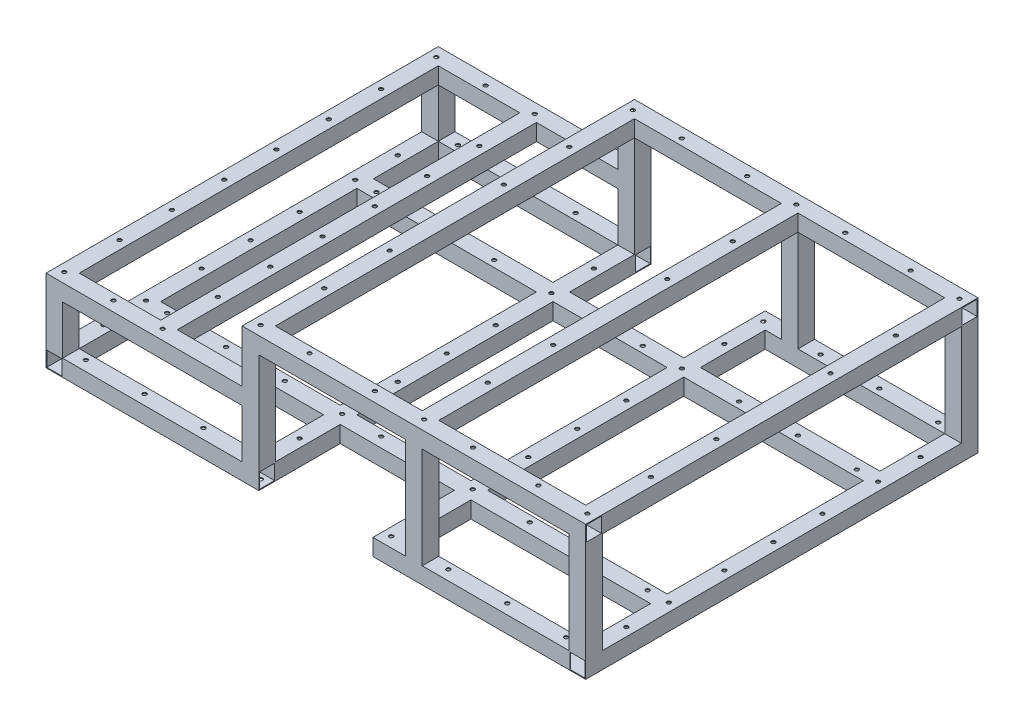
SolidWorks part; units mm, degrees
ref_plane "Front Plane" through (0, 0, 0) normal (0, 0, 1) x (1, 0, 0)
ref_plane "Top Plane" through (0, 0, 0) normal (0, 1, 0) x (1, 0, 0)
ref_plane "Right Plane" through (0, 0, 0) normal (1, 0, 0) x (0, 0, -1)
sketch "Sketch1" plane through (0, 0, 0) normal (0, 1, 0) x (1, 0, 0)
  line L0 (0, 0) -> (-415.7612, 0) construction
  line L1 (-387.3, -150) -> (387.3, -150)
  line L2 (-387.3, -150) -> (-387.3, -175.4)
  line L3 (-387.3, -175.4) -> (387.3, -175.4)
  line L4 (387.3, -150) -> (387.3, -175.4)
  line L9 (0, 0) -> (0, -321.173) construction
  line L10 (387.3, 150) -> (387.3, 175.4)
  line L11 (-387.3, 175.4) -> (387.3, 175.4)
  line L12 (-387.3, 150) -> (-387.3, 175.4)
  line L13 (-387.3, 150) -> (387.3, 150)
  point P7 (0, -175.4)
  dimension "D1" = 774.6
  dimension "D2" = 25.4
  dimension "D3" = 150
  dimension "D4" = 0
extrude "Boss-Extrude1" add sketch "Sketch1" along normal blind 25.4
sketch "Sketch4" plane through (-387.3, 0, 0) normal (-1, 0, 0) x (0, 0, 1)
  line L0 (-175.4, 25.4) -> (-150, 25.4) construction
  line L1 (-174.2, 24.2) -> (-151.2, 24.2)
  line L2 (-174.2, 24.2) -> (-174.2, 1.2)
  line L3 (-174.2, 1.2) -> (-151.2, 1.2)
  line L4 (-151.2, 24.2) -> (-151.2, 1.2)
  line L5 (-150, 25.4) -> (-150, 0) construction
  line L6 (-175.4, 0) -> (-150, 0) construction
  line L7 (-175.4, 25.4) -> (-175.4, 0) construction
  line L8 (0, 0) -> (0, 21.4103) construction
  line L9 (174.2, 1.2) -> (151.2, 1.2)
  line L10 (151.2, 24.2) -> (151.2, 1.2)
  line L11 (174.2, 24.2) -> (151.2, 24.2)
  line L12 (174.2, 24.2) -> (174.2, 1.2)
  dimension "D1" = 1.2
  dimension "D2" = 1.2
  dimension "D3" = 1.2
  dimension "D4" = 1.2
extrude "Cut-Extrude2" cut sketch "Sketch4" against normal up to next (774.6 mm away)
sketch "Sketch2" plane through (0, 0, 0) normal (0, -1, 0) x (1, 0, 0)
  line L0 (0, 0) -> (0, -349.2287) construction
  line L1 (412.7, 300) -> (387.3, 300)
  line L2 (412.7, 300) -> (412.7, -300)
  line L3 (412.7, -300) -> (387.3, -300)
  line L4 (387.3, 300) -> (387.3, -300)
  line L5 (0, 0) -> (432.1136, 0) construction
  line L6 (387.3, -150) -> (387.3, -175.4) construction
  line L7 (-387.3, 300) -> (-387.3, -300)
  line L8 (-412.7, -300) -> (-387.3, -300)
  line L9 (-412.7, 300) -> (-412.7, -300)
  line L10 (-412.7, 300) -> (-387.3, 300)
  point P10 (387.3, 0)
  dimension "D1" = 25.4
  dimension "D2" = 600
  dimension "D3" = 25.4
  dimension "D4" = 0
extrude "Boss-Extrude2" add sketch "Sketch2" against normal blind 25.4
sketch "Sketch3" plane through (0, 0, -300) normal (0, 0, -1) x (-1, 0, 0)
  line L0 (-387.3, 25.4) -> (-412.7, 25.4) construction
  line L1 (-411.5, 24.2) -> (-388.5, 24.2)
  line L2 (-411.5, 24.2) -> (-411.5, 1.2)
  line L3 (-411.5, 1.2) -> (-388.5, 1.2)
  line L4 (-388.5, 24.2) -> (-388.5, 1.2)
  line L5 (-387.3, 25.4) -> (-387.3, 0) construction
  line L6 (-387.3, 0) -> (-412.7, 0) construction
  line L7 (-412.7, 25.4) -> (-412.7, 0) construction
  line L8 (0, 0) -> (0, 119.739) construction
  line L9 (388.5, 24.2) -> (388.5, 1.2)
  line L10 (411.5, 1.2) -> (388.5, 1.2)
  line L11 (411.5, 24.2) -> (411.5, 1.2)
  line L12 (411.5, 24.2) -> (388.5, 24.2)
  point P10 (-400, 0)
  dimension "D1" = 1.2
  dimension "D2" = 1.2
  dimension "D3" = 1.2
  dimension "D4" = 1.2
extrude "Cut-Extrude1" cut sketch "Sketch3" against normal up to next
sketch "Sketch6" plane through (-387.3, 0, 0) normal (1, 0, 0) x (0, 0, -1)
  line L0 (300, 0) -> (175.4, 0) construction
  line L1 (300, 25.4) -> (274.6, 25.4)
  line L2 (300, 25.4) -> (300, 0)
  line L3 (300, 0) -> (274.6, 0)
  line L4 (274.6, 25.4) -> (274.6, 0)
  line L5 (0, 0) -> (0, 25.4) construction
  line L6 (150, 0) -> (-150, 0) construction
  line L7 (150, 25.4) -> (-150, 25.4) construction
  line L13 (-274.6, 25.4) -> (-274.6, 0)
  line L14 (-300, 0) -> (-274.6, 0)
  line L15 (-300, 25.4) -> (-300, 0)
  line L16 (-300, 25.4) -> (-274.6, 25.4)
  dimension "D1" = 25.4
extrude "Boss-Extrude3" add sketch "Sketch6" along normal blind 300
sketch "Sketch7" plane through (387.3, 0, 0) normal (-1, 0, 0) x (0, 0, 1)
  line L0 (-175.4, 25.4) -> (-300, 25.4) construction
  line L1 (-300, 0) -> (-274.6, 0)
  line L2 (-300, 0) -> (-300, 25.4)
  line L3 (-300, 25.4) -> (-274.6, 25.4)
  line L4 (-274.6, 0) -> (-274.6, 25.4)
  line L10 (0, 0) -> (0, 25.4) construction
  line L11 (150, 0) -> (-150, 0) construction
  line L12 (150, 25.4) -> (-150, 25.4) construction
  line L13 (274.6, 0) -> (274.6, 25.4)
  line L14 (300, 25.4) -> (274.6, 25.4)
  line L15 (300, 0) -> (300, 25.4)
  line L16 (300, 0) -> (274.6, 0)
  dimension "D1" = 25.4
extrude "Boss-Extrude4" add sketch "Sketch7" along normal blind 300
ref_plane "Plane1" through (0, 0, 0) normal (1, 0, 0) x (0, 0, -1)
sketch "Sketch8" plane through (0, 0, 0) normal (1, 0, 0) x (0, 0, -1)
  line L4 (-275.8, 24.2) -> (-298.8, 24.2)
  line L5 (-298.8, 24.2) -> (-298.8, 1.2)
  line L6 (-298.8, 1.2) -> (-275.8, 1.2)
  line L7 (-275.8, 1.2) -> (-275.8, 24.2)
  line L8 (-274.6, 25.4) -> (-300, 25.4)
  line L9 (-300, 25.4) -> (-300, 0)
  line L10 (-300, 0) -> (-274.6, 0)
  line L11 (-274.6, 0) -> (-274.6, 25.4)
  line L12 (-274.6, 25.4) -> (-300, 25.4)
  line L13 (-300, 25.4) -> (-300, 0)
  line L14 (-300, 0) -> (-274.6, 0)
  line L15 (-274.6, 0) -> (-274.6, 25.4)
  line L16 (300, 0) -> (300, 25.4)
  line L17 (300, 25.4) -> (274.6, 25.4)
  line L18 (274.6, 25.4) -> (274.6, 0)
  line L19 (274.6, 0) -> (300, 0)
  line L20 (300, 0) -> (300, 25.4)
  line L21 (300, 25.4) -> (274.6, 25.4)
  line L22 (274.6, 25.4) -> (274.6, 0)
  line L23 (274.6, 0) -> (300, 0)
  line L24 (298.8, 1.2) -> (298.8, 24.2)
  line L25 (298.8, 24.2) -> (275.8, 24.2)
  line L26 (275.8, 24.2) -> (275.8, 1.2)
  line L27 (275.8, 1.2) -> (298.8, 1.2)
  dimension "D1" = 0
  dimension "D2" = 0
  dimension "D3" = 1.2
  dimension "D4" = 1.2
extrude "Cut-Extrude4" cut sketch "Sketch8" against normal up to surface and the other way up to vertex (388.5 mm away) contours L24 L25 L26 L27 | L7 L4 L5 L6 up to face at (-388.5, 12.7, 0)
sketch "Sketch9" plane through (0, 0, -274.6) normal (0, 0, 1) x (1, 0, 0)
  line L0 (-87.3, 25.4) -> (-387.3, 25.4) construction
  line L1 (-87.3, 0) -> (-112.7, 0)
  line L2 (-87.3, 0) -> (-87.3, 25.4)
  line L3 (-87.3, 25.4) -> (-112.7, 25.4)
  line L4 (-112.7, 0) -> (-112.7, 25.4)
  line L5 (-87.3, 0) -> (87.3, 0) construction
  line L6 (-87.3, 25.4) -> (87.3, 25.4) construction
  line L7 (0, 25.4) -> (0, 0) construction
  line L12 (-88.5, 1.2) -> (-111.5, 1.2)
  line L13 (-111.5, 1.2) -> (-111.5, 24.2)
  line L14 (-88.5, 24.2) -> (-111.5, 24.2)
  line L15 (-88.5, 1.2) -> (-88.5, 24.2)
  line L16 (88.5, 1.2) -> (88.5, 24.2)
  line L17 (88.5, 24.2) -> (111.5, 24.2)
  line L18 (87.3, 25.4) -> (112.7, 25.4)
  line L19 (87.3, 0) -> (87.3, 25.4)
  line L20 (111.5, 1.2) -> (111.5, 24.2)
  line L21 (88.5, 1.2) -> (111.5, 1.2)
  line L22 (112.7, 0) -> (112.7, 25.4)
  line L23 (87.3, 0) -> (112.7, 0)
  dimension "D1" = 25.4
  dimension "D2" = 1.2
extrude "Boss-Extrude5" add sketch "Sketch9" along normal up to surface (550.4 mm away) up to face at (-237.9, 12.7, 275.8)
sketch "Sketch11" plane through (0, 25.4, 0) normal (0, 1, 0) x (1, 0, 0)
  line L0 (-412.7, 0) -> (0, 0) construction
  line L1 (-412.7, 300) -> (-387.3, 300)
  line L2 (-412.7, 300) -> (-412.7, 274.6)
  line L3 (-412.7, 274.6) -> (-387.3, 274.6)
  line L4 (-387.3, 300) -> (-387.3, 274.6)
  line L5 (-412.7, -300) -> (-412.7, 300) construction
  line L7 (-411.5, 298.8) -> (-388.5, 298.8)
  line L8 (-388.5, 298.8) -> (-388.5, 275.8)
  line L9 (-411.5, 275.8) -> (-388.5, 275.8)
  line L10 (-411.5, 298.8) -> (-411.5, 275.8)
  line L11 (-411.5, -298.8) -> (-411.5, -275.8)
  line L12 (-411.5, -275.8) -> (-388.5, -275.8)
  line L13 (-388.5, -298.8) -> (-388.5, -275.8)
  line L14 (-411.5, -298.8) -> (-388.5, -298.8)
  line L15 (-387.3, -300) -> (-387.3, -274.6)
  line L16 (-412.7, -274.6) -> (-387.3, -274.6)
  line L17 (-412.7, -300) -> (-412.7, -274.6)
  line L18 (-412.7, -300) -> (-387.3, -300)
  dimension "D1" = 1.2
extrude "Boss-Extrude6" add sketch "Sketch11" along normal blind 74.6
sketch "Sketch12" plane through (0, 25.4, 0) normal (0, 1, 0) x (1, 0, 0)
  line L0 (-88.5, 298.8) -> (-111.5, 298.8)
  line L1 (-87.3, 300) -> (-112.7, 300)
  line L2 (-87.3, 300) -> (-87.3, 274.6)
  line L3 (-87.3, 274.6) -> (-112.7, 274.6)
  line L4 (-112.7, 300) -> (-112.7, 274.6)
  line L5 (-111.5, 298.8) -> (-111.5, 275.8)
  line L6 (-88.5, 275.8) -> (-111.5, 275.8)
  line L7 (-88.5, 298.8) -> (-88.5, 275.8)
  line L8 (-112.7, 0) -> (412.7, 0) construction
  line L10 (-112.7, -150) -> (-112.7, 150) construction
  line L11 (412.7, 300) -> (412.7, -300) construction
  line L12 (150, 0) -> (150, 300) construction
  line L13 (87.3, 300) -> (412.7, 300) construction
  line L14 (-88.5, -298.8) -> (-88.5, -275.8)
  line L15 (-88.5, -275.8) -> (-111.5, -275.8)
  line L16 (-111.5, -298.8) -> (-111.5, -275.8)
  line L17 (-112.7, -300) -> (-112.7, -274.6)
  line L18 (-87.3, -274.6) -> (-112.7, -274.6)
  line L19 (-87.3, -300) -> (-87.3, -274.6)
  line L20 (-87.3, -300) -> (-112.7, -300)
  line L21 (-88.5, -298.8) -> (-111.5, -298.8)
  line L22 (388.5, -298.8) -> (411.5, -298.8)
  line L23 (387.3, -300) -> (412.7, -300)
  line L24 (387.3, -300) -> (387.3, -274.6)
  line L25 (387.3, -274.6) -> (412.7, -274.6)
  line L26 (412.7, -300) -> (412.7, -274.6)
  line L27 (411.5, -298.8) -> (411.5, -275.8)
  line L28 (388.5, -275.8) -> (411.5, -275.8)
  line L29 (388.5, -298.8) -> (388.5, -275.8)
  line L30 (388.5, 298.8) -> (388.5, 275.8)
  line L31 (388.5, 275.8) -> (411.5, 275.8)
  line L32 (411.5, 298.8) -> (411.5, 275.8)
  line L33 (412.7, 300) -> (412.7, 274.6)
  line L34 (387.3, 274.6) -> (412.7, 274.6)
  line L35 (387.3, 300) -> (387.3, 274.6)
  line L36 (387.3, 300) -> (412.7, 300)
  line L37 (388.5, 298.8) -> (411.5, 298.8)
  line L38 (112.7, 274.6) -> (387.3, 274.6) construction
  line L39 (137.3, 300) -> (162.7, 300)
  line L40 (137.3, 300) -> (137.3, 274.6)
  line L41 (137.3, 274.6) -> (162.7, 274.6)
  line L42 (162.7, 300) -> (162.7, 274.6)
  line L47 (138.5, 298.8) -> (161.5, 298.8)
  line L48 (161.5, 298.8) -> (161.5, 275.8)
  line L49 (138.5, 275.8) -> (161.5, 275.8)
  line L50 (138.5, 298.8) -> (138.5, 275.8)
  line L51 (138.5, -298.8) -> (138.5, -275.8)
  line L52 (138.5, -275.8) -> (161.5, -275.8)
  line L53 (161.5, -298.8) -> (161.5, -275.8)
  line L54 (138.5, -298.8) -> (161.5, -298.8)
  line L55 (162.7, -300) -> (162.7, -274.6)
  line L56 (137.3, -274.6) -> (162.7, -274.6)
  line L57 (137.3, -300) -> (137.3, -274.6)
  line L58 (137.3, -300) -> (162.7, -300)
  line L59 (87.3, 175.4) -> (87.3, 300) construction
  dimension "D2" = 50
  dimension "D3" = 25.4
  dimension "D1" = 1.2
  dimension "D4" = 1.2
extrude "Boss-Extrude7" add sketch "Sketch12" along normal blind 154.6
sketch "Sketch13" plane through (0, 180, 0) normal (0, 1, 0) x (1, 0, 0)
  line L0 (-87.3, 274.6) -> (-87.3, -274.6) construction
  line L1 (-112.7, -300) -> (412.7, -300)
  line L2 (-112.7, -300) -> (-112.7, -274.6)
  line L3 (-112.7, -274.6) -> (412.7, -274.6)
  line L4 (412.7, -300) -> (412.7, -274.6)
  line L5 (-87.3, 0) -> (0, 0) construction
  line L6 (412.7, 300) -> (412.7, 274.6)
  line L7 (-112.7, 274.6) -> (412.7, 274.6)
  line L8 (-112.7, 300) -> (-112.7, 274.6)
  line L9 (-112.7, 300) -> (412.7, 300)
extrude "Boss-Extrude9" add sketch "Sketch13" along normal blind 25.4
sketch "Sketch14" plane through (-112.7, 0, 0) normal (-1, 0, 0) x (0, 0, 1)
  line L0 (-300, 205.4) -> (-274.6, 205.4) construction
  line L1 (-298.8, 204.2) -> (-275.8, 204.2)
  line L2 (-298.8, 204.2) -> (-298.8, 181.2)
  line L3 (-298.8, 181.2) -> (-275.8, 181.2)
  line L4 (-275.8, 204.2) -> (-275.8, 181.2)
  line L5 (-300, 205.4) -> (-300, 25.4) construction
  line L6 (-274.6, 205.4) -> (-274.6, 25.4) construction
  line L7 (-300, 180) -> (-274.6, 180) construction
  line L8 (-274.6, 180) -> (274.6, 180) construction
  line L9 (274.6, 205.4) -> (274.6, 25.4) construction
  line L10 (0, 180) -> (0, 204.2) construction
  line L11 (300, 180) -> (274.6, 180) construction
  line L12 (275.8, 204.2) -> (275.8, 181.2)
  line L13 (298.8, 181.2) -> (275.8, 181.2)
  line L14 (298.8, 204.2) -> (298.8, 181.2)
  line L15 (298.8, 204.2) -> (275.8, 204.2)
  dimension "D1" = 1.2
  dimension "D2" = 1.2
  dimension "D3" = 1.2
  dimension "D4" = 25.4
  dimension "D5" = 1.2
extrude "Cut-Extrude5" cut sketch "Sketch14" against normal up to surface (525.4 mm away) up to face at (412.7, 109.05, 0)
sketch "Sketch15" plane through (0, 0, -274.6) normal (0, 0, 1) x (1, 0, 0)
  line L0 (-112.7, 205.4) -> (412.7, 205.4) construction
  line L1 (-112.7, 205.4) -> (-87.3, 205.4)
  line L2 (-112.7, 205.4) -> (-112.7, 180)
  line L3 (-112.7, 180) -> (-87.3, 180)
  line L4 (-87.3, 205.4) -> (-87.3, 180)
  line L5 (137.3, 180) -> (162.7, 180)
  line L6 (137.3, 180) -> (137.3, 205.4)
  line L7 (137.3, 205.4) -> (162.7, 205.4)
  line L8 (162.7, 180) -> (162.7, 205.4)
  line L9 (-111.5, 204.2) -> (-88.5, 204.2)
  line L10 (387.3, 180) -> (412.7, 180)
  line L11 (387.3, 180) -> (387.3, 205.4)
  line L12 (387.3, 205.4) -> (412.7, 205.4)
  line L13 (412.7, 180) -> (412.7, 205.4)
  line L14 (-88.5, 204.2) -> (-88.5, 181.2)
  line L15 (-111.5, 181.2) -> (-88.5, 181.2)
  line L16 (-111.5, 204.2) -> (-111.5, 181.2)
  line L17 (138.5, 181.2) -> (161.5, 181.2)
  line L18 (161.5, 181.2) -> (161.5, 204.2)
  line L19 (138.5, 204.2) -> (161.5, 204.2)
  line L20 (138.5, 181.2) -> (138.5, 204.2)
  line L21 (388.5, 181.2) -> (411.5, 181.2)
  line L22 (411.5, 181.2) -> (411.5, 204.2)
  line L23 (388.5, 204.2) -> (411.5, 204.2)
  line L24 (388.5, 181.2) -> (388.5, 204.2)
  dimension "D1" = 1.2
extrude "Boss-Extrude10" add sketch "Sketch15" along normal up to surface (549.2 mm away) up to face at (100, 12.7, 274.6)
sketch "Sketch16" plane through (-412.7, 0, 0) normal (-1, 0, 0) x (0, 0, 1)
  line L0 (275.8, 101.2) -> (298.8, 101.2)
  line L1 (274.6, 100) -> (300, 100)
  line L2 (274.6, 100) -> (274.6, 125.4)
  line L3 (274.6, 125.4) -> (300, 125.4)
  line L4 (300, 100) -> (300, 125.4)
  line L5 (298.8, 101.2) -> (298.8, 124.2)
  line L6 (275.8, 124.2) -> (298.8, 124.2)
  line L7 (275.8, 101.2) -> (275.8, 124.2)
  line L8 (-274.6, 100) -> (274.6, 100) construction
  line L9 (0, 100) -> (0, 0) construction
  line L11 (300, 0) -> (-300, 0) construction
  line L12 (-275.8, 101.2) -> (-275.8, 124.2)
  line L13 (-275.8, 124.2) -> (-298.8, 124.2)
  line L14 (-298.8, 101.2) -> (-298.8, 124.2)
  line L15 (-300, 100) -> (-300, 125.4)
  line L16 (-274.6, 125.4) -> (-300, 125.4)
  line L17 (-274.6, 100) -> (-274.6, 125.4)
  line L18 (-274.6, 100) -> (-300, 100)
  line L19 (-275.8, 101.2) -> (-298.8, 101.2)
  dimension "D1" = 25.4
  dimension "D2" = 25.4
  dimension "D3" = 1.2
extrude "Boss-Extrude11" add sketch "Sketch16" against normal up to surface (300 mm away) up to face at (-112.7, 192.7, -287.3)
sketch "Sketch17" plane through (0, 0, 274.6) normal (0, 0, -1) x (-1, 0, 0)
  line L0 (112.7, 100) -> (387.3, 100) construction
  line L1 (387.3, 100) -> (412.7, 100)
  line L2 (387.3, 100) -> (387.3, 125.4)
  line L3 (387.3, 125.4) -> (412.7, 125.4)
  line L4 (412.7, 100) -> (412.7, 125.4)
  line L5 (250, 100) -> (250, 125.4) construction
  line L6 (112.7, 125.4) -> (412.7, 125.4) construction
  line L7 (238.5, 124.2) -> (261.5, 124.2)
  line L8 (237.3, 125.4) -> (262.7, 125.4)
  line L9 (237.3, 125.4) -> (237.3, 100)
  line L10 (237.3, 100) -> (262.7, 100)
  line L11 (262.7, 125.4) -> (262.7, 100)
  line L12 (261.5, 124.2) -> (261.5, 101.2)
  line L13 (238.5, 101.2) -> (261.5, 101.2)
  line L14 (238.5, 124.2) -> (238.5, 101.2)
  line L16 (388.5, 101.2) -> (411.5, 101.2)
  line L17 (411.5, 101.2) -> (411.5, 124.2)
  line L18 (388.5, 124.2) -> (411.5, 124.2)
  line L19 (388.5, 101.2) -> (388.5, 124.2)
  dimension "D1" = 25.4
  dimension "D2" = 12.7
  dimension "D3" = 1.2
  dimension "D4" = 1.2
extrude "Boss-Extrude12" add sketch "Sketch17" along normal up to surface (549.2 mm away) up to face at (-100, 192.7, -274.6)
sketch "Sketch18" plane through (0, 25.4, 0) normal (0, 1, 0) x (1, 0, 0)
  line L0 (162.7, 274.6) -> (387.3, 274.6) construction
  line L1 (387.3, 300) -> (387.3, 274.6) construction
  line L2 (112.7, 274.6) -> (137.3, 274.6) construction
  line L3 (87.3, 175.4) -> (87.3, 300) construction
  line L4 (387.3, -150) -> (387.3, 150) construction
  line L5 (112.7, 150) -> (387.3, 150) construction
  line L6 (87.3, -150) -> (87.3, 150) construction
  line L7 (412.7, 0) -> (0, 0) construction
  line L8 (412.7, 274.6) -> (412.7, -274.6) construction
  line L9 (0, 0) -> (0, 303.2716) construction
  line L10 (87.3, 300) -> (137.3, 300) construction
  line L11 (387.3, 175.4) -> (387.3, 274.6) construction
  line L12 (388.5, 300) -> (411.5, 300) construction
  line L13 (411.5, 300) -> (388.5, 300) construction
  line L14 (87.3, 300) -> (412.7, 300) construction
  line L15 (-87.3, 150) -> (87.3, 150) construction
  circle A0 centre (367.3, 284.6) radius 3
  circle A1 centre (277.3, 284.6) radius 3
  circle A2 centre (187.3, 284.6) radius 3
  circle A3 centre (99.8, 284.6) radius 3
  circle A4 centre (367.3, 160) radius 3
  circle A5 centre (277.3, 160) radius 3
  circle A6 centre (187.3, 160) radius 3
  circle A7 centre (99.8, 160) radius 3
  circle A8 centre (99.8, 225) radius 3
  circle A9 centre (399.8, 225) radius 3
  circle A11 centre (399.8, 0) radius 3
  circle A12 centre (399.8, 75) radius 3
  circle A13 centre (99.8, 0) radius 3
  circle A14 centre (99.8, 75) radius 3
  circle A15 centre (399.8, 160) radius 3
  circle A16 centre (40, 160) radius 3
  circle A17 centre (-40, 160) radius 3
  circle A18 centre (-399.8, 160) radius 3
  circle A19 centre (-99.8, 75) radius 3
  circle A20 centre (-99.8, 0) radius 3
  circle A21 centre (-399.8, 75) radius 3
  circle A22 centre (-399.8, 0) radius 3
  circle A23 centre (-399.8, 225) radius 3
  circle A24 centre (-99.8, 225) radius 3
  circle A25 centre (-99.8, 160) radius 3
  circle A26 centre (-187.3, 160) radius 3
  circle A27 centre (-277.3, 160) radius 3
  circle A28 centre (-367.3, 160) radius 3
  circle A29 centre (-99.8, 284.6) radius 3
  circle A30 centre (-187.3, 284.6) radius 3
  circle A31 centre (-277.3, 284.6) radius 3
  circle A32 centre (-367.3, 284.6) radius 3
  circle A33 centre (-367.3, -284.6) radius 3
  circle A34 centre (-277.3, -284.6) radius 3
  circle A35 centre (-187.3, -284.6) radius 3
  circle A36 centre (-99.8, -284.6) radius 3
  circle A37 centre (-367.3, -160) radius 3
  circle A38 centre (-277.3, -160) radius 3
  circle A39 centre (-187.3, -160) radius 3
  circle A40 centre (-99.8, -160) radius 3
  circle A41 centre (-99.8, -225) radius 3
  circle A42 centre (-399.8, -225) radius 3
  circle A43 centre (-399.8, -75) radius 3
  circle A44 centre (-99.8, -75) radius 3
  circle A45 centre (-399.8, -160) radius 3
  circle A46 centre (-40, -160) radius 3
  circle A47 centre (40, -160) radius 3
  circle A48 centre (399.8, -160) radius 3
  circle A49 centre (99.8, -75) radius 3
  circle A50 centre (399.8, -75) radius 3
  circle A51 centre (399.8, -225) radius 3
  circle A52 centre (99.8, -225) radius 3
  circle A53 centre (99.8, -160) radius 3
  circle A54 centre (187.3, -160) radius 3
  circle A55 centre (277.3, -160) radius 3
  circle A56 centre (367.3, -160) radius 3
  circle A57 centre (99.8, -284.6) radius 3
  circle A58 centre (187.3, -284.6) radius 3
  circle A59 centre (277.3, -284.6) radius 3
  circle A60 centre (367.3, -284.6) radius 3
  dimension "D1" = 10
  dimension "D5" = 6
  dimension "D6" = 6
  dimension "D7" = 10
  dimension "D9" = 6
  dimension "D10" = 6
  dimension "D13" = 6
  dimension "D14" = 6
  dimension "D15" = 6
  dimension "D22" = 6
  dimension "D27" = 6
  dimension "D28" = 6
  dimension "D29" = 12.5
  dimension "D30" = 75
  dimension "D33" = 6
  dimension "D34" = 6
  dimension "D35" = 6
  dimension "D36" = 6
  dimension "D43" = 6
  dimension "D44" = 12.5
  dimension "D46" = 6
  dimension "D2" = 20
  dimension "D3" = 10
  dimension "D4" = 110
  dimension "D8" = 200
  dimension "D11" = 10
  dimension "D12" = 12.5
  dimension "D16" = 20
  dimension "D17" = 10
  dimension "D18" = 110
  dimension "D19" = 10
  dimension "D20" = 10
  dimension "D21" = 200
  dimension "D23" = 10
  dimension "D24" = 12.5
  dimension "D25" = 12.5
  dimension "D26" = 75
  dimension "D31" = 12.5
  dimension "D32" = 300
  dimension "D37" = 12.5
  dimension "D38" = 12.5
  dimension "D39" = 225
  dimension "D40" = 300
  dimension "D41" = 225
  dimension "D42" = 12.5
  dimension "D45" = 10
  dimension "D47" = 10
  dimension "D48" = 40
extrude "Cut-Extrude6" cut sketch "Sketch18" against normal up to surface (25.4 mm away) up to face at (0, 0, 0)
sketch "Sketch20" plane through (0, 205.4, 0) normal (0, 1, 0) x (1, 0, 0)
  line L0 (387.3, 0) -> (162.7, 0) construction
  line L1 (387.3, -274.6) -> (387.3, 274.6) construction
  line L2 (162.7, -274.6) -> (162.7, 274.6) construction
  line L3 (412.7, 300) -> (-112.7, 300) construction
  line L4 (150, 300) -> (150, -300) construction
  line L5 (-112.7, -300) -> (412.7, -300) construction
  line L6 (275, 274.6) -> (275, 0) construction
  line L7 (162.7, 274.6) -> (387.3, 274.6) construction
  line L8 (275, 137.3) -> (387.3, 137.3) construction
  circle A0 centre (399.8, 284.6) radius 3
  circle A2 centre (399.8, 187.3) radius 3
  circle A3 centre (325, 284.6) radius 3
  circle A4 centre (225, 284.6) radius 3
  circle A5 centre (150.2, 187.3) radius 3
  circle A6 centre (150.2, 284.6) radius 3
  circle A7 centre (150.2, 87.3) radius 3
  circle A8 centre (399.8, 87.3) radius 3
  circle A9 centre (399.8, -87.3) radius 3
  circle A10 centre (150.2, -87.3) radius 3
  circle A11 centre (150.2, -284.6) radius 3
  circle A12 centre (150.2, -187.3) radius 3
  circle A13 centre (225, -284.6) radius 3
  circle A14 centre (325, -284.6) radius 3
  circle A15 centre (399.8, -187.3) radius 3
  circle A16 centre (399.8, -284.6) radius 3
  circle A17 centre (-99.8, -284.6) radius 3
  circle A18 centre (-99.8, -187.3) radius 3
  circle A19 centre (-25, -284.6) radius 3
  circle A20 centre (75, -284.6) radius 3
  circle A21 centre (-99.8, -87.3) radius 3
  circle A22 centre (-99.8, 87.3) radius 3
  circle A23 centre (75, 284.6) radius 3
  circle A24 centre (-25, 284.6) radius 3
  circle A25 centre (-99.8, 187.3) radius 3
  circle A26 centre (-99.8, 284.6) radius 3
  dimension "D1" = 6
  dimension "D6" = 6
  dimension "D7" = 6
  dimension "D2" = 10
  dimension "D3" = 12.5
  dimension "D4" = 10
  dimension "D5" = 50
  dimension "D8" = 50
  dimension "D9" = 12.5
extrude "Cut-Extrude7" cut sketch "Sketch20" against normal up to next (1.2 mm away)
sketch "Sketch21" plane through (0, 125.4, 0) normal (0, 1, 0) x (1, 0, 0)
  line L0 (-262.7, 0) -> (-387.3, 0) construction
  line L1 (-262.7, 274.6) -> (-262.7, -274.6) construction
  line L2 (-387.3, 274.6) -> (-387.3, -274.6) construction
  line L3 (-325, 274.6) -> (-325, 0) construction
  line L4 (-262.7, 274.6) -> (-387.3, 274.6) construction
  line L5 (-412.7, -300) -> (-412.7, 300) construction
  line L6 (-112.7, 300) -> (-412.7, 300) construction
  circle A0 centre (-400.2, 284.6) radius 3
  circle A1 centre (-324.995, 284.6) radius 3
  circle A2 centre (-400.2, 200) radius 3
  circle A3 centre (-400.2, 120) radius 3
  circle A4 centre (-400.2, 40) radius 3
  circle A5 centre (-249.8, 40) radius 3
  circle A6 centre (-249.8, 120) radius 3
  circle A7 centre (-249.8, 200) radius 3
  circle A8 centre (-249.8, 284.6) radius 3
  circle A9 centre (-249.8, -284.6) radius 3
  circle A10 centre (-249.8, -200) radius 3
  circle A11 centre (-249.8, -120) radius 3
  circle A12 centre (-400.2, -40) radius 3
  circle A13 centre (-400.2, -120) radius 3
  circle A14 centre (-400.2, -200) radius 3
  circle A15 centre (-324.995, -284.6) radius 3
  circle A16 centre (-400.2, -284.6) radius 3
  circle A17 centre (-249.8, -40) radius 3
  dimension "D1" = 12.5
  dimension "D3" = 6
  dimension "D4" = 6
  dimension "D5" = 10
  dimension "D8" = 6
  dimension "D9" = 6
  dimension "D13" = 12.5
  dimension "D14" = 6
  dimension "D2" = 10
  dimension "D6" = 0.01
  dimension "D7" = 12.5
  dimension "D10" = 12.5
  dimension "D11" = 100
  dimension "D12" = 120
  dimension "D15" = 40
extrude "Cut-Extrude8" cut sketch "Sketch21" against normal up to next
equation "\"thi\"=1.2"
equation "\"D5@Sketch14\"=\"thi\""
equation "\"D2@Sketch14\"=\"thi\""
equation "\"D3@Sketch14\"=\"thi\""
equation "\"D1@Sketch14\"=\"thi\""
